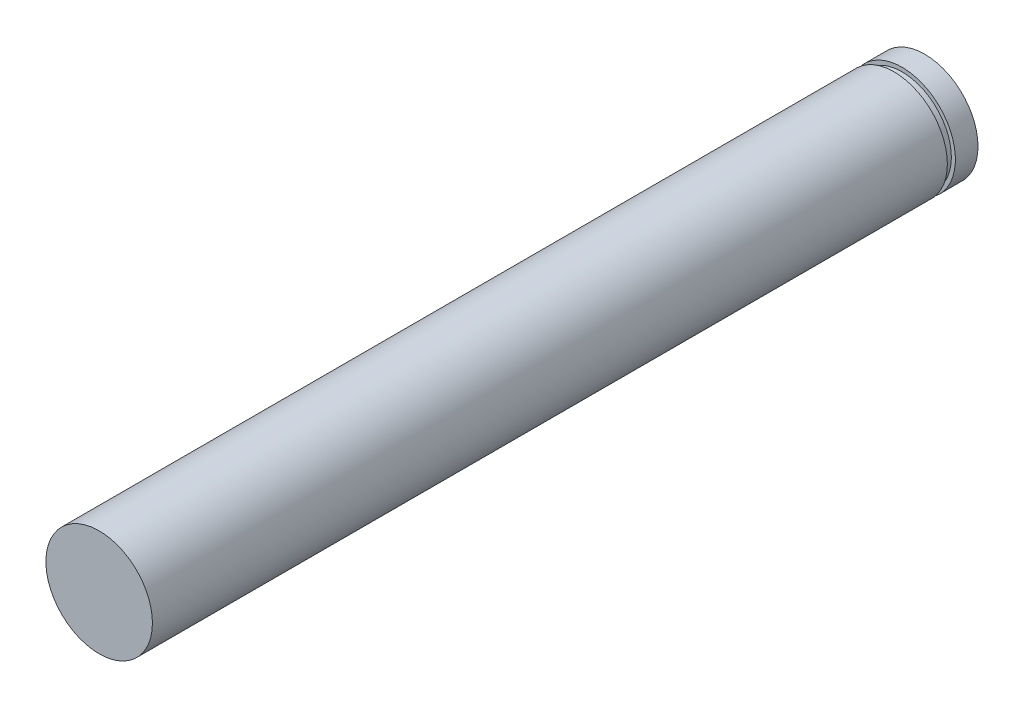
SolidWorks part; units mm, degrees
ref_plane "Front Plane" through (0, 0, 0) normal (0, 0, 1) x (1, 0, 0)
ref_plane "Top Plane" through (0, 0, 0) normal (0, 1, 0) x (1, 0, 0)
ref_plane "Right Plane" through (0, 0, 0) normal (1, 0, 0) x (0, 0, -1)
sketch "Sketch1" plane through (0, 0, 0) normal (0, 0, 1) x (1, 0, 0)
  circle A0 centre (0, 0) radius 4
  dimension "D1" = 8
extrude "Boss-Extrude1" add sketch "Sketch1" along normal blind 62
sketch "Sketch2" plane through (0, 0, 0) normal (0, 1, 0) x (1, 0, 0)
  line L0 (4, -62) -> (4, 0) construction
  line L1 (3.7, -1.7) -> (4.3, -1.7)
  line L2 (3.7, -1.7) -> (3.7, -2.3)
  line L3 (3.7, -2.3) -> (4.3, -2.3)
  line L4 (4.3, -1.7) -> (4.3, -2.3)
  line L5 (3.7, -1.7) -> (4.3, -2.3) construction
  line L6 (3.7, -2.3) -> (4.3, -1.7) construction
  line L7 (4, 0) -> (-4, 0) construction
  point P0 (4, -2)
  dimension "D1" = 2
  dimension "D2" = 3.7
  dimension "D3" = 0.6
ref_axis "Axis1" through (0, 0, 62) along (0, 0, -1)
revolve "Cut-Revolve1" cut sketch "Sketch2" angle 360 about axis through (0, 0, 62) along (0, 0, -1)
